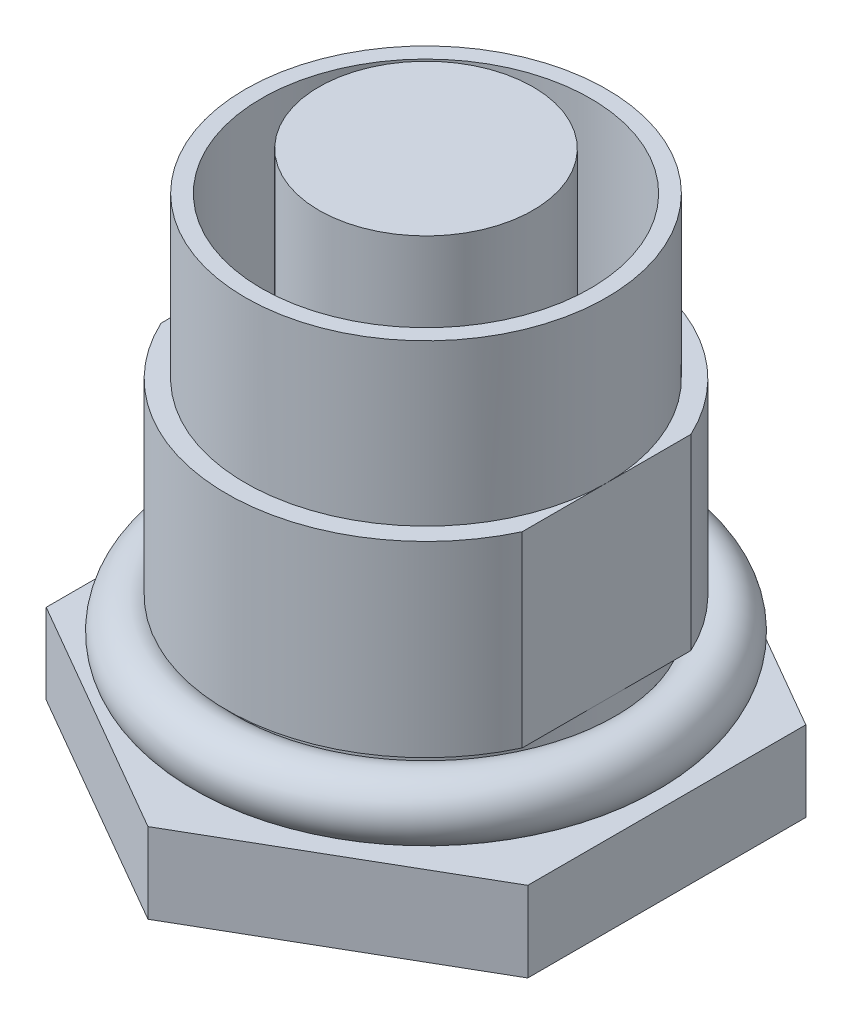
SolidWorks part; units mm, degrees
ref_plane "Front Plane" through (0, 0, 0) normal (0, 0, 1) x (1, 0, 0)
ref_plane "Top Plane" through (0, 0, 0) normal (0, 1, 0) x (1, 0, 0)
ref_plane "Right Plane" through (0, 0, 0) normal (1, 0, 0) x (0, 0, -1)
sketch "Sketch1" plane through (0, 0, 0) normal (0, 1, 0) x (1, 0, 0)
  circle A0 centre (0, 0) radius 6.75
extrude "Boss-Extrude1" add sketch "Sketch1" along normal blind 18.3
sketch "Sketch2" plane through (0, 0, 0) normal (0, -1, 0) x (1, 0, 0)
  line L1 (0, 10.3923) -> (-9, 5.1962)
  line L2 (-9, 5.1962) -> (-9, -5.1962)
  line L3 (-9, -5.1962) -> (0, -10.3923)
  line L4 (0, -10.3923) -> (9, -5.1962)
  line L5 (9, -5.1962) -> (9, 5.1962)
  line L6 (9, 5.1962) -> (0, 10.3923)
  circle A0 centre (0, 0) radius 9 construction
  dimension "D1" = 18
extrude "Boss-Extrude2" add sketch "Sketch2" against normal blind 3
sketch "Sketch3" plane through (0, 18.3, 0) normal (0, 1, 0) x (1, 0, 0)
  circle A0 centre (0, 0) radius 6.75 construction
  circle A1 centre (0, 0) radius 6.75
  circle A2 centre (0, 0) radius 6.15
  dimension "D1" = 0.6
extrude "Cut-Extrude1" cut sketch "Sketch3" against normal up to surface (15.3 mm away) contours A2 up to face at (0, 3, -6.75)
sketch "Sketch4" plane through (0, 3, 0) normal (0, 1, 0) x (1, 0, 0)
  circle A0 centre (0, 0) radius 4
extrude "Boss-Extrude3" add sketch "Sketch4" along normal blind 16.75
sketch "Sketch5" plane through (0, 0, 0) normal (0, 0, 1) x (1, 0, 0)
  line L0 (0, -2.6335) -> (0, 23.0835) construction
  line L1 (-6.75, 3) -> (-6.75, 18.3)
  line L2 (6.75, 18.3) -> (6.75, 3)
  line L3 (6.75, 18.3) -> (6.75, 3)
  line L4 (-6.75, 3) -> (-6.75, 18.3)
  line L5 (-9, 3) -> (-6.75, 3)
  line L6 (6.75, 3) -> (9, 3)
  line L7 (6.75, 3) -> (9, 3)
  line L8 (-9, 3) -> (-6.75, 3)
  line L9 (-9, 3) -> (-9, 0)
  line L10 (-9, 3) -> (-9, 0)
  line L11 (-7.875, 3) -> (-7.875, 6.4688) construction
  circle A0 centre (-7.875, 4.125) radius 1.125
revolve "Revolve1" add sketch "Sketch5" angle 360 about L0
ref_plane "Plane1" through (0, 12.3, 0) normal (0, 1, 0) x (1, 0, 0)
sketch "Sketch6" plane through (0, 12.3, 0) normal (0, 1, 0) x (1, 0, 0)
  line L0 (-6.75, 0) -> (-6.75, 3.1528)
  line L1 (-6.75, 3.1528) -> (-6.75, -3.1528)
  line L2 (6.75, 0) -> (6.75, 3.1528)
  line L3 (6.75, 3.1528) -> (6.75, -3.1528)
  circle A0 centre (0, 0) radius 6.75
  circle A1 centre (0, 0) radius 6.75
  arc A2 (6.75, 3.1528) -> (-6.75, 3.1528) centre (0, 0) ccw
  arc A3 (-6.75, -3.1528) -> (6.75, -3.1528) centre (0, 0) ccw
extrude "Boss-Extrude4" add sketch "Sketch6" against normal blind 7 contours L2 A2 L0 A1 | L1 A3 L3 A1
